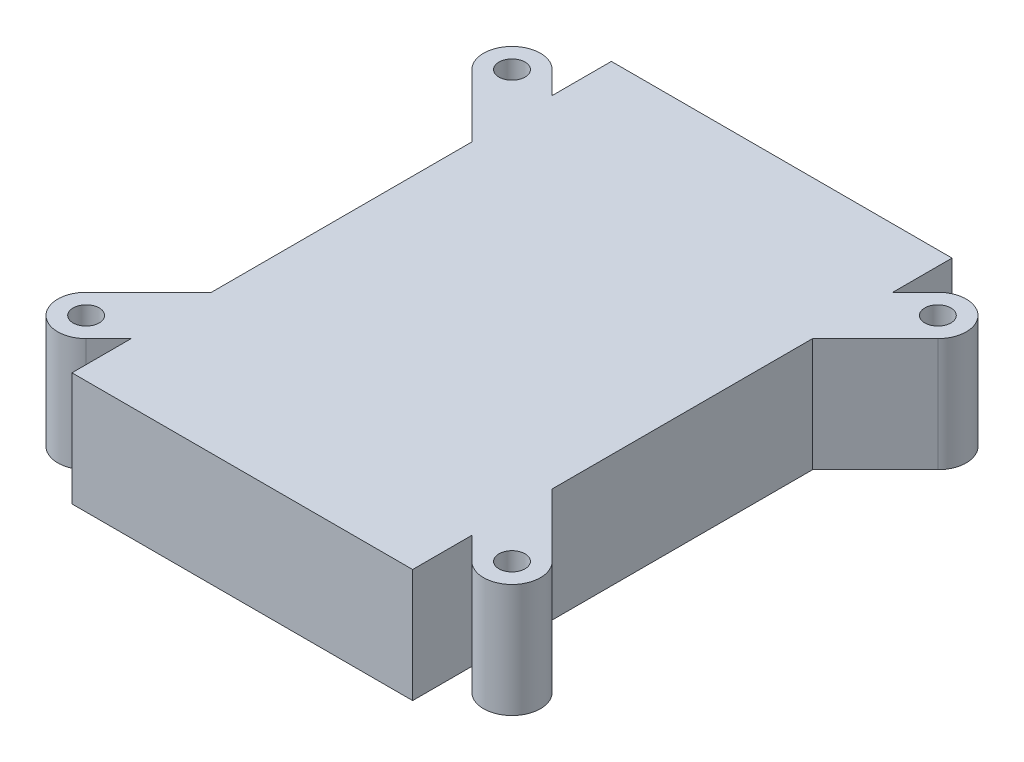
SolidWorks part; units mm, degrees
ref_plane "Plan de face" through (0, 0, 0) normal (0, 0, 1) x (1, 0, 0)
ref_plane "Plan de dessus" through (0, 0, 0) normal (0, 1, 0) x (1, 0, 0)
ref_plane "Plan de droite" through (0, 0, 0) normal (1, 0, 0) x (0, 0, -1)
sketch "Esquisse1" plane through (0, 0, 0) normal (0, 1, 0) x (1, 0, 0)
  line L0 (0, 0) -> (0, 37.5) construction
  line L1 (0, 37.5) -> (37.5, 37.5) construction
  line L2 (0, 37.5) -> (-37.5, 37.5) construction
  line L3 (-37.5, 37.5) -> (-37.5, -37.5) construction
  line L4 (-37.5, -37.5) -> (37.5, -37.5) construction
  line L5 (37.5, -37.5) -> (37.5, 37.5) construction
  line L6 (0, 37.5) -> (0, 47.5) construction
  line L7 (0, 47.5) -> (-30, 47.5)
  line L8 (-30, 47.5) -> (-30, -47.5)
  line L9 (-30, -47.5) -> (30, -47.5)
  line L10 (30, -47.5) -> (30, 47.5)
  line L11 (30, 47.5) -> (0, 47.5)
  line L12 (-37.5, 37.5) -> (-41.0355, 33.9645) construction
  line L13 (-41.0355, 33.9645) -> (-30, 22.9289)
  line L14 (-37.5, 37.5) -> (-33.9645, 41.0355)
  line L15 (-33.9645, 41.0355) -> (-30, 37.0711)
  line L16 (37.5, 37.5) -> (41.0355, 33.9645)
  line L17 (41.0355, 33.9645) -> (30, 22.9289)
  line L18 (33.9645, 41.0355) -> (30, 37.0711)
  line L19 (-30, 22.9289) -> (-30, 37.0711)
  line L20 (30, 37.0711) -> (30, 22.9289)
  line L21 (-37.5, -37.5) -> (-41.0355, -33.9645)
  line L22 (-41.0355, -33.9645) -> (-30, -22.9289)
  line L23 (-33.9645, -41.0355) -> (-30, -37.0711)
  line L24 (-30, -37.0711) -> (-30, -22.9289)
  line L25 (37.5, -37.5) -> (41.0355, -33.9645)
  line L26 (41.0355, -33.9645) -> (30, -22.9289)
  line L27 (37.5, -37.5) -> (33.9645, -41.0355)
  line L28 (33.9645, -41.0355) -> (30, -37.0711)
  line L29 (30, -37.0711) -> (30, -22.9289)
  line L30 (-37.5, -37.5) -> (-33.9645, -41.0355)
  line L31 (-41.0355, 33.9645) -> (-37.5, 37.5)
  line L32 (33.9645, 41.0355) -> (37.5, 37.5)
  circle A0 centre (-37.5, 37.5) radius 2.3
  circle A1 centre (37.5, 37.5) radius 2.3
  circle A2 centre (37.5, -37.5) radius 2.3
  circle A3 centre (-37.5, -37.5) radius 2.3
  circle A4 centre (-37.5, 37.5) radius 5
  circle A5 centre (37.5, 37.5) radius 5
  circle A6 centre (-37.5, -37.5) radius 5
  circle A7 centre (37.5, -37.5) radius 5
extrude "Boss.-Extru.1" add sketch "Esquisse1" along normal blind 20 contours L10 L11 L7 L8 L9 | A6 L23 L8 L22 | L30 A6 L21 A3 | L21 A6 L30 A3 | L27 A7 L25 A2 | L25 A7 L27 A2 | A7 L26 L10 L28 | A5 L18 L10 L17 | L16 A5 L32 A1 | L32 A5 L16 A1 | A4 L13 L8 L15 | L31 A4 L14 A0 | L14 A4 L31 A0
